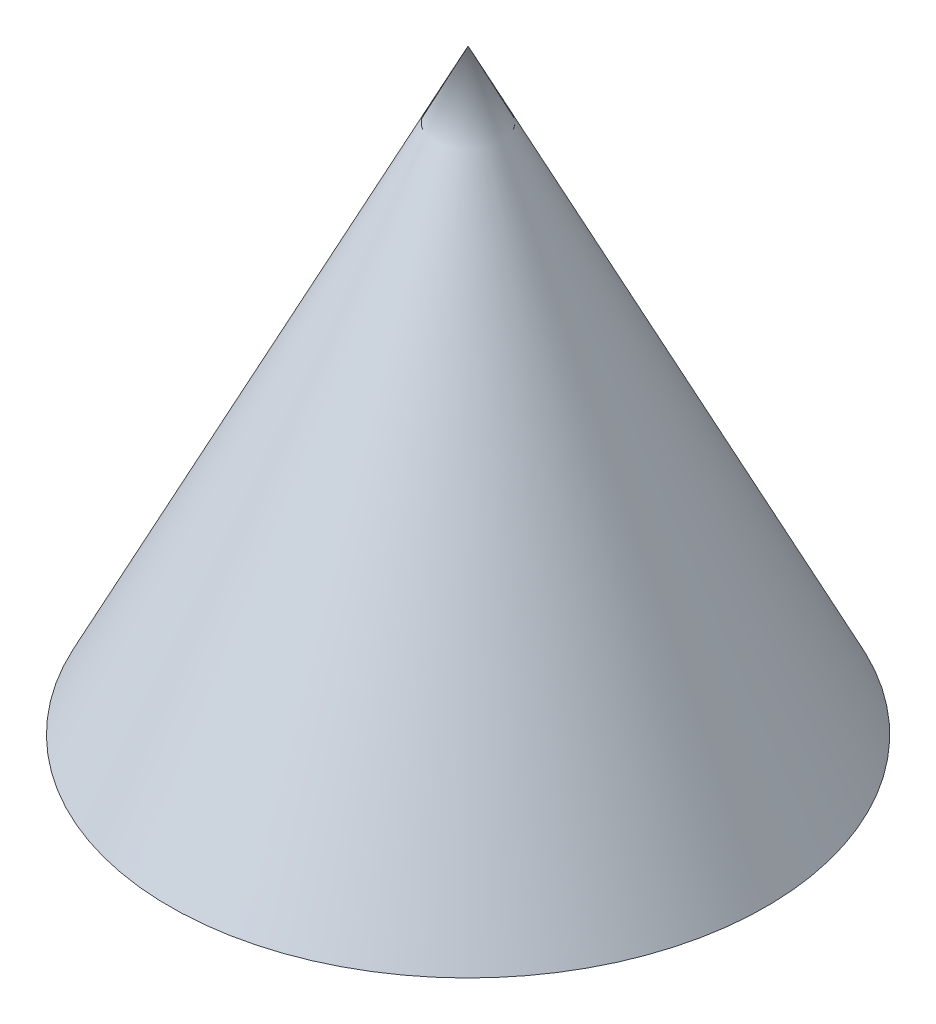
SolidWorks part; units mm, degrees
ref_plane "Front Plane" through (0, 0, 0) normal (0, 0, 1) x (1, 0, 0)
ref_plane "Top Plane" through (0, 0, 0) normal (0, 1, 0) x (1, 0, 0)
ref_plane "Right Plane" through (0, 0, 0) normal (1, 0, 0) x (0, 0, -1)
sketch "Sketch1" plane through (0, 0, 0) normal (0, 0, 1) x (1, 0, 0)
  line L0 (0, 0) -> (0, 10) construction
  line L1 (0, 0) -> (5, 0)
  line L2 (5, 0) -> (0, 10)
  line L3 (0, 0) -> (0, 10)
revolve "Revolve1" add sketch "Sketch1" angle 360 about L0
